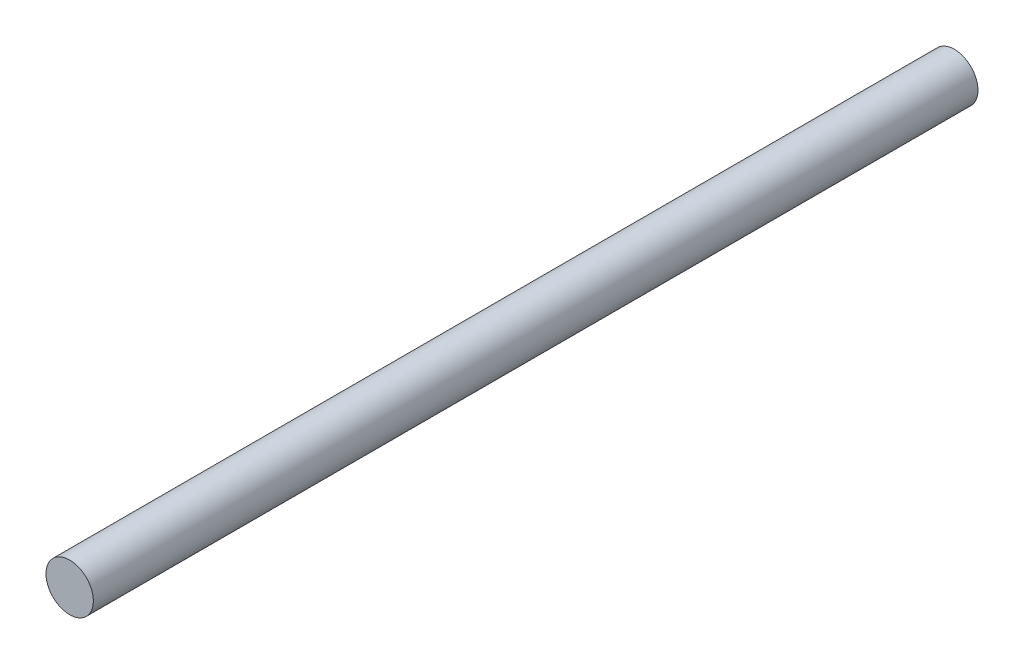
SolidWorks part; units mm, degrees
ref_plane "Front Plane" through (0, 0, 0) normal (0, 0, 1) x (1, 0, 0)
ref_plane "Top Plane" through (0, 0, 0) normal (0, 1, 0) x (1, 0, 0)
ref_plane "Right Plane" through (0, 0, 0) normal (1, 0, 0) x (0, 0, -1)
sketch "Sketch1" plane through (0, 0, 0) normal (0, 0, 1) x (1, 0, 0)
  circle A0 centre (0, 0) radius 28.575
  dimension "D1" = 57.15
extrude "Boss-Extrude1" add sketch "Sketch1" along normal blind 1066.8
